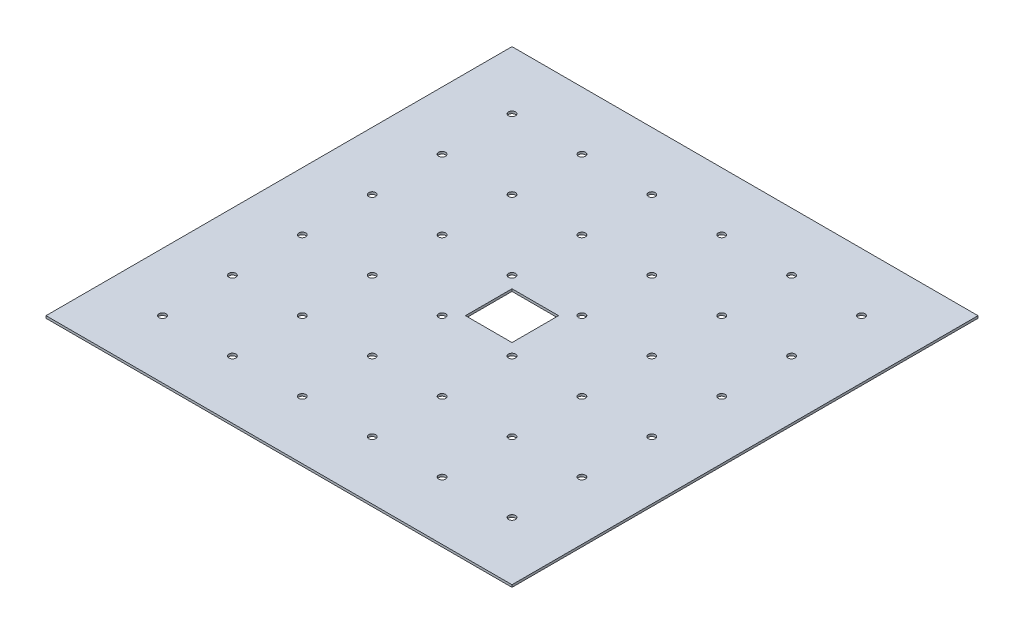
SolidWorks part; units mm, degrees
ref_plane "Front Plane" through (0, 0, 0) normal (0, 0, 1) x (1, 0, 0)
ref_plane "Top Plane" through (0, 0, 0) normal (0, 1, 0) x (1, 0, 0)
ref_plane "Right Plane" through (0, 0, 0) normal (1, 0, 0) x (0, 0, -1)
sketch "Sketch1" plane through (0, 0, 0) normal (0, 1, 0) x (1, 0, 0)
  line L1 (-200, 200) -> (200, 200)
  line L2 (-200, 200) -> (-200, -200)
  line L3 (-200, -200) -> (200, -200)
  line L4 (200, 200) -> (200, -200)
  line L5 (-200, 200) -> (200, -200) construction
  line L6 (-200, -200) -> (200, 200) construction
  point P0 (0, 0)
  dimension "D1" = 400
  dimension "D2" = 400
extrude "Boss-Extrude1" add sketch "Sketch1" along normal blind 2
sketch "Sketch2" plane through (0, 2, 0) normal (0, 1, 0) x (1, 0, 0)
  line L0 (-200, 0) -> (200, 0) construction
  line L1 (-200, 200) -> (-200, -200) construction
  line L2 (200, -200) -> (200, 200) construction
  line L3 (0, 200) -> (0, -200) construction
  line L4 (200, 200) -> (-200, 200) construction
  line L5 (-200, -200) -> (200, -200) construction
  line L6 (-150, 150) -> (-200, 150) construction
  line L7 (-150, 150) -> (-150, 200) construction
  line L8 (-150, 150) -> (-90, 150) construction
  line L9 (-150, 150) -> (-150, 90) construction
  line L10 (-150, -150) -> (-150, -200) construction
  line L11 (150, -150) -> (200, -150) construction
  circle A0 centre (-150, 150) radius 3
  circle A1 centre (-90, 150) radius 3
  circle A2 centre (-30, 150) radius 3
  circle A3 centre (30, 150) radius 3
  circle A4 centre (90, 150) radius 3
  circle A5 centre (150, 150) radius 3
  circle A6 centre (-90, 90) radius 3
  circle A7 centre (-30, 90) radius 3
  circle A8 centre (30, 90) radius 3
  circle A9 centre (90, 90) radius 3
  circle A10 centre (150, 90) radius 3
  circle A11 centre (-90, 30) radius 3
  circle A12 centre (-30, 30) radius 3
  circle A13 centre (30, 30) radius 3
  circle A14 centre (90, 30) radius 3
  circle A15 centre (150, 30) radius 3
  circle A16 centre (-90, -30) radius 3
  circle A17 centre (-30, -30) radius 3
  circle A18 centre (30, -30) radius 3
  circle A19 centre (90, -30) radius 3
  circle A20 centre (150, -30) radius 3
  circle A21 centre (-90, -90) radius 3
  circle A22 centre (-30, -90) radius 3
  circle A23 centre (30, -90) radius 3
  circle A24 centre (90, -90) radius 3
  circle A25 centre (150, -90) radius 3
  circle A26 centre (-90, -150) radius 3
  circle A27 centre (-30, -150) radius 3
  circle A28 centre (30, -150) radius 3
  circle A29 centre (90, -150) radius 3
  circle A30 centre (150, -150) radius 3
  circle A31 centre (-150, 90) radius 3
  circle A32 centre (-150, 30) radius 3
  circle A33 centre (-150, -30) radius 3
  circle A34 centre (-150, -90) radius 3
  circle A35 centre (-150, -150) radius 3
  dimension "D1" = 6
  dimension "D4" = 90
  dimension "D5" = 60
  dimension "D6" = 60
  dimension "D2" = 6
  dimension "D3" = 6
extrude "Cut-Extrude1" cut sketch "Sketch2" against normal through all
sketch "Sketch3" plane through (0, 2, 0) normal (0, 1, 0) x (1, 0, 0)
  line L1 (-20, 20) -> (20, 20)
  line L2 (-20, 20) -> (-20, -20)
  line L3 (-20, -20) -> (20, -20)
  line L4 (20, 20) -> (20, -20)
  line L5 (-20, 20) -> (20, -20) construction
  line L6 (-20, -20) -> (20, 20) construction
  point P0 (0, 0)
  dimension "D1" = 40
  dimension "D2" = 40
extrude "Cut-Extrude2" cut sketch "Sketch3" against normal through all
